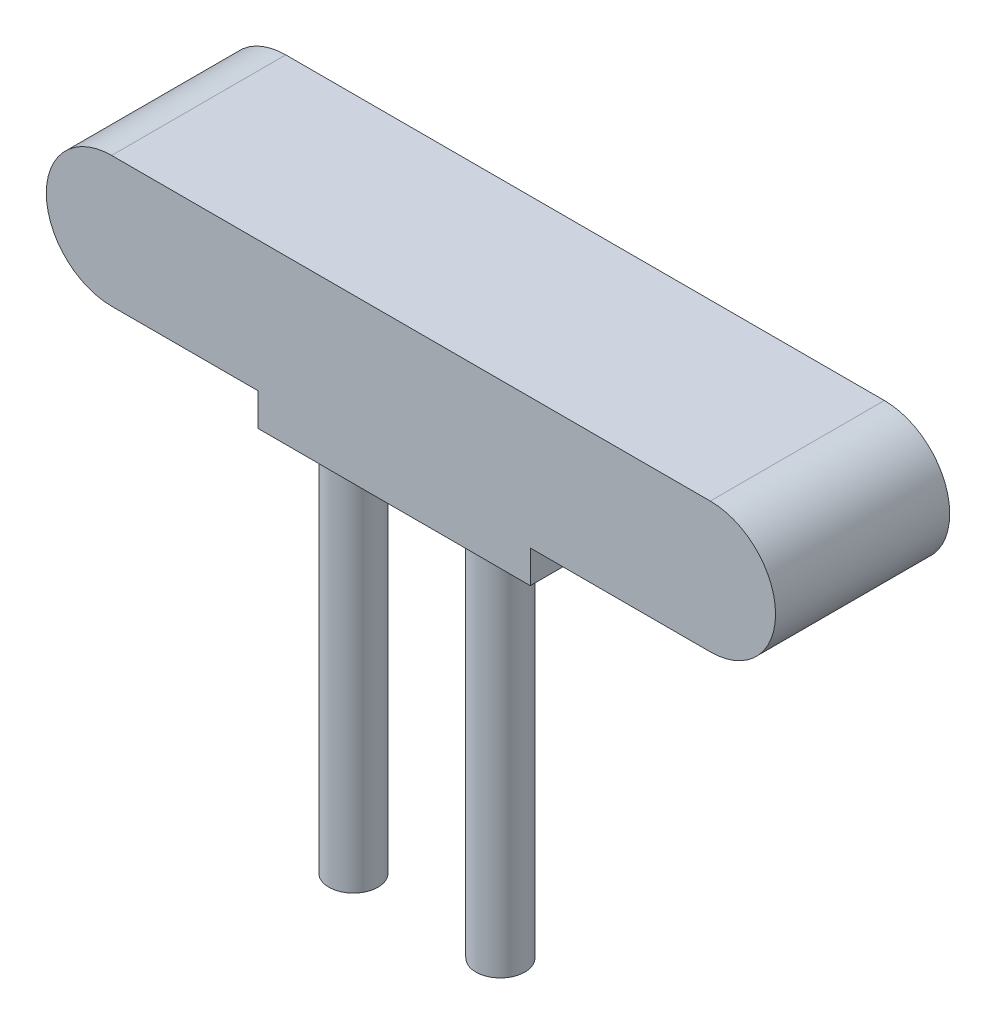
SolidWorks part; units mm, degrees
ref_plane "Front Plane" through (0, 0, 0) normal (0, 0, 1) x (1, 0, 0)
ref_plane "Top Plane" through (0, 0, 0) normal (0, 1, 0) x (1, 0, 0)
ref_plane "Right Plane" through (0, 0, 0) normal (1, 0, 0) x (0, 0, -1)
sketch "Sketch1" plane through (0, 0, 0) normal (0, 1, 0) x (1, 0, 0)
  line L1 (0, 0) -> (63.5, 0)
  line L2 (0, 0) -> (0, 15.24)
  line L3 (0, 15.24) -> (63.5, 15.24)
  line L4 (63.5, 0) -> (63.5, 15.24)
  dimension "D1" = 63.5
  dimension "D2" = 15.24
extrude "Boss-Extrude1" add sketch "Sketch1" along normal blind 7.62
sketch "Sketch2" plane through (0, 0, 0) normal (0, 0, 1) x (1, 0, 0)
  line L5 (0, 7.62) -> (63.5, 7.62) construction
  line L6 (-34.21, 38.1) -> (105.49, 38.1)
  line L8 (-34.21, 7.62) -> (105.49, 7.62)
  arc A0 (105.49, 7.62) -> (105.49, 38.1) centre (105.49, 22.86) ccw
  arc A1 (-34.21, 38.1) -> (-34.21, 7.62) centre (-34.21, 22.86) ccw
  dimension "D2" = 30.48
  dimension "D3" = 0
extrude "Boss-Extrude2" add sketch "Sketch2" against normal blind 40.64
sketch "Sketch3" plane through (0, 0, 0) normal (0, -1, 0) x (1, 0, 0)
  line L1 (0, 0) -> (63.5, 0) construction
  line L2 (0, -15.24) -> (0, 0) construction
  circle A0 centre (14.605, -7.62) radius 5.715
  circle A1 centre (48.895, -7.62) radius 5.715
  point P9 (31.75, 0)
  point P10 (0, -7.62)
  dimension "D1" = 11.43
  dimension "D2" = 11.43
  dimension "D3" = 0
  dimension "D4" = 34.29
  dimension "D5" = 17.145
  dimension "D6" = 0
extrude "Boss-Extrude3" add sketch "Sketch3" along normal blind 86.36
sketch "Sketch4" plane through (0, -86.36, 0) normal (0, -1, 0) x (1, 0, 0)
  circle A0 centre (14.605, -7.62) radius 1.905
  circle A1 centre (48.895, -7.62) radius 1.905
  dimension "D1" = 3.81
  dimension "D2" = 3.81
extrude "Cut-Extrude1" cut sketch "Sketch4" against normal blind 12.7
